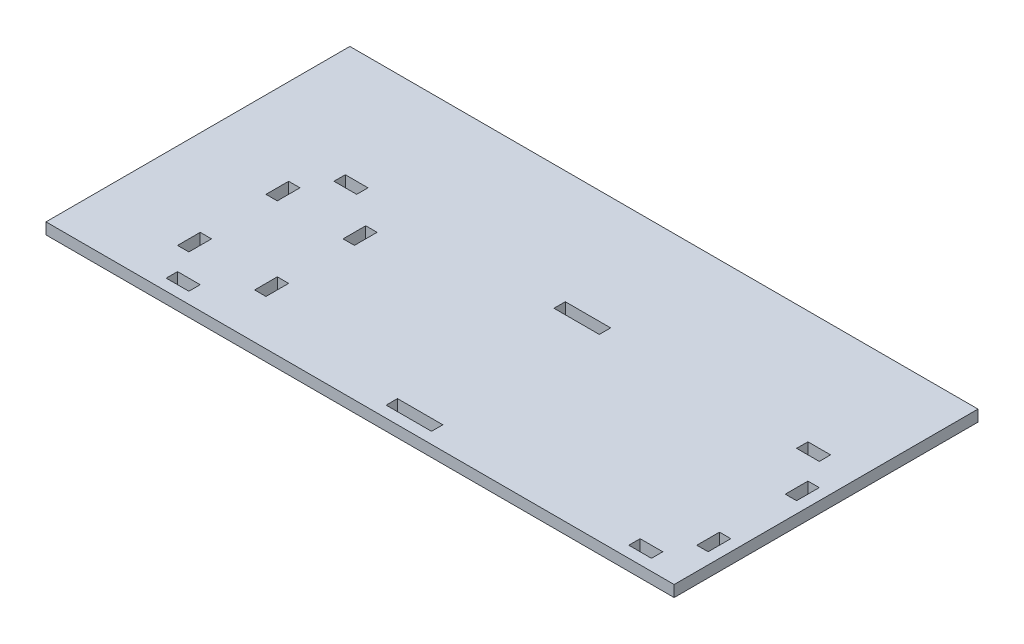
SolidWorks part; units mm, degrees
ref_plane "前视基准面" through (0, 0, 0) normal (0, 0, 1) x (1, 0, 0)
ref_plane "上视基准面" through (0, 0, 0) normal (0, 1, 0) x (1, 0, 0)
ref_plane "右视基准面" through (0, 0, 0) normal (1, 0, 0) x (0, 0, -1)
sketch "草图1" plane through (0, 0, 0) normal (0, 1, 0) x (1, 0, 0)
  line L0 (102.2985, -38.9462) -> (-220.1525, -38.9462) construction
  line L1 (-195.0587, 90.0538) -> (76.9413, 90.0538)
  line L2 (-195.0587, 90.0538) -> (-195.0587, -43.9462)
  line L3 (-195.0587, -43.9462) -> (76.9413, -43.9462)
  line L4 (-123.0587, 51.5868) -> (-123.0587, -58.8534) construction
  line L5 (-157.0587, 112.183) -> (-157.0587, -66.2942) construction
  line L6 (-227.3669, 40.0538) -> (127.2494, 40.0538) construction
  line L7 (56.9413, 40.0538) -> (66.9413, 40.0538)
  line L8 (-147.0587, 40.0538) -> (-137.0587, 40.0538)
  line L9 (-147.0587, 40.0538) -> (-147.0587, 35.0538)
  line L10 (-147.0587, 35.0538) -> (-137.0587, 35.0538)
  line L11 (-137.0587, 40.0538) -> (-137.0587, 35.0538)
  line L12 (56.9413, 40.0538) -> (56.9413, 35.0538)
  line L13 (56.9413, 35.0538) -> (66.9413, 35.0538)
  line L14 (66.9413, 40.0538) -> (66.9413, 35.0538)
  line L15 (-157.0587, 40.0538) -> (76.9413, -33.9462) construction
  line L16 (-147.0587, -38.9462) -> (-137.0587, -38.9462)
  line L17 (-147.0587, -38.9462) -> (-147.0587, -33.9462)
  line L18 (-147.0587, -33.9462) -> (-137.0587, -33.9462)
  line L19 (-137.0587, -38.9462) -> (-137.0587, -33.9462)
  line L20 (66.9413, -38.9462) -> (56.9413, -38.9462)
  line L21 (66.9413, -38.9462) -> (66.9413, -33.9462)
  line L22 (66.9413, -33.9462) -> (56.9413, -33.9462)
  line L23 (56.9413, -38.9462) -> (56.9413, -33.9462)
  line L24 (76.9413, 40.0538) -> (-157.0587, -38.9462) construction
  line L25 (-40.0587, 3.0538) -> (-40.0587, -68.5298) construction
  line L26 (-40.0587, 3.0538) -> (-40.0587, 66.6502) construction
  line L27 (76.9413, 90.0538) -> (81.9413, 90.0538)
  line L28 (-50.0587, 40.0538) -> (-30.0587, 40.0538)
  line L29 (-50.0587, 40.0538) -> (-50.0587, 35.0538)
  line L30 (-50.0587, 35.0538) -> (-30.0587, 35.0538)
  line L31 (-30.0587, 40.0538) -> (-30.0587, 35.0538)
  line L32 (-157.0587, 25.0538) -> (-152.0587, 25.0538)
  line L33 (-157.0587, 25.0538) -> (-157.0587, 15.0538)
  line L34 (-157.0587, 15.0538) -> (-152.0587, 15.0538)
  line L35 (-152.0587, 25.0538) -> (-152.0587, 15.0538)
  line L36 (-157.0587, -23.9462) -> (-152.0587, -23.9462)
  line L37 (-157.0587, -23.9462) -> (-157.0587, -13.9462)
  line L38 (-157.0587, -13.9462) -> (-152.0587, -13.9462)
  line L39 (-152.0587, -23.9462) -> (-152.0587, -13.9462)
  line L40 (76.9413, 25.0538) -> (71.9413, 25.0538)
  line L41 (76.9413, 25.0538) -> (76.9413, 15.0538)
  line L42 (76.9413, 15.0538) -> (71.9413, 15.0538)
  line L43 (71.9413, 25.0538) -> (71.9413, 15.0538)
  line L44 (76.9413, -23.9462) -> (71.9413, -23.9462)
  line L45 (76.9413, -23.9462) -> (76.9413, -13.9462)
  line L46 (76.9413, -13.9462) -> (71.9413, -13.9462)
  line L47 (71.9413, -23.9462) -> (71.9413, -13.9462)
  line L48 (81.9413, 90.0538) -> (81.9413, -43.9462)
  line L49 (81.9413, -43.9462) -> (76.9413, -43.9462)
  line L50 (-50.0587, -38.9462) -> (-30.0587, -38.9462)
  line L51 (-50.0587, -38.9462) -> (-50.0587, -33.9462)
  line L52 (-50.0587, -33.9462) -> (-30.0587, -33.9462)
  line L53 (-30.0587, -38.9462) -> (-30.0587, -33.9462)
  line L54 (76.9413, -13.9462) -> (76.9413, -23.9462)
  line L55 (76.9413, 25.0538) -> (76.9413, 15.0538)
  line L56 (-118.0587, 51.5868) -> (-118.0587, -63.9291) construction
  line L58 (-123.0587, 25.0538) -> (-118.0587, 25.0538)
  line L59 (-123.0587, 25.0538) -> (-123.0587, 15.0538)
  line L60 (-123.0587, 15.0538) -> (-118.0587, 15.0538)
  line L61 (-118.0587, 25.0538) -> (-118.0587, 15.0538)
  line L62 (-123.0587, -23.9462) -> (-118.0587, -23.9462)
  line L63 (-123.0587, -23.9462) -> (-123.0587, -13.9462)
  line L64 (-123.0587, -13.9462) -> (-118.0587, -13.9462)
  line L65 (-118.0587, -23.9462) -> (-118.0587, -13.9462)
  point P27 (74.4413, 25.0538)
  dimension "D2" = 134
  dimension "D4" = 5
  dimension "D5" = 79
  dimension "D6" = 10
  dimension "D7" = 5
  dimension "D8" = 10
  dimension "D9" = 5
  dimension "D10" = 10
  dimension "D11" = 277
  dimension "D12" = 5
  dimension "D13" = 10
  dimension "D14" = 10
  dimension "D15" = 5
  dimension "D16" = 10
  dimension "D17" = 5
  dimension "D18" = 10
  dimension "D19" = 5
  dimension "D20" = 15
  dimension "D21" = 15
  dimension "D22" = 10
  dimension "D23" = 10
  dimension "D24" = 5
  dimension "D25" = 10
  dimension "D26" = 15
  dimension "D27" = 15
  dimension "D28" = 15
  dimension "D29" = 5
  dimension "D30" = 20
  dimension "D31" = 10
  dimension "D32" = 20
  dimension "D33" = 5
  dimension "D34" = 10
  dimension "D35" = 15
  dimension "D36" = 29
  dimension "D37" = 5
  dimension "D38" = 15
  dimension "D39" = 10
extrude "凸台-拉伸1" add sketch "草图1" along normal blind 5 contours L49 L48 L27 L1 L2 L3 L53 L50 L51 L52 L43 L40 L41 L42 L39 L36 L37 L38 L19 L16 L17 L18 L8 L11 L10 L9 L7 L14 L13 L12 L20 L23 L22 L21 L28 L31 L30 L29 L32 L35 L34 L33
